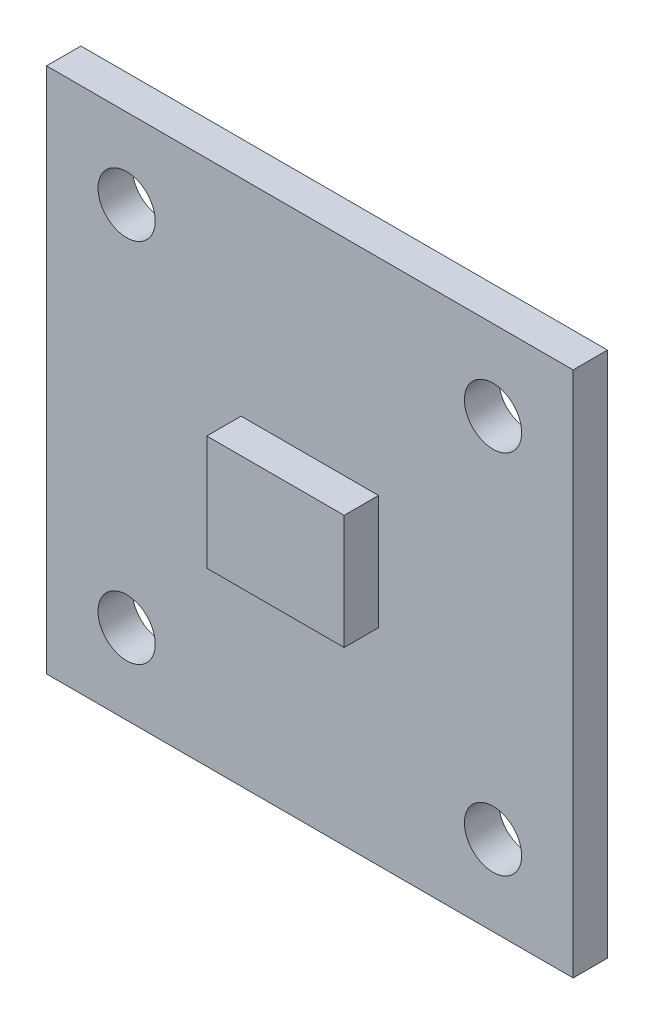
SolidWorks part; units mm, degrees
ref_plane "前视基准面" through (0, 0, 0) normal (0, 0, 1) x (1, 0, 0)
ref_plane "上视基准面" through (0, 0, 0) normal (0, 1, 0) x (1, 0, 0)
ref_plane "右视基准面" through (0, 0, 0) normal (1, 0, 0) x (0, 0, -1)
sketch "草图1" plane through (0, 0, 0) normal (0, 0, 1) x (1, 0, 0)
  line L1 (-11.5, -11.5) -> (11.5, -11.5)
  line L2 (-11.5, -11.5) -> (-11.5, 11.5)
  line L3 (-11.5, 11.5) -> (11.5, 11.5)
  line L4 (11.5, -11.5) -> (11.5, 11.5)
  line L5 (-11.5, -11.5) -> (11.5, 11.5) construction
  line L6 (-11.5, 11.5) -> (11.5, -11.5) construction
  line L7 (-8, -8) -> (8, -8) construction
  line L8 (-8, -8) -> (-8, 8) construction
  line L9 (-8, 8) -> (8, 8) construction
  line L10 (8, -8) -> (8, 8) construction
  line L11 (-8, -8) -> (8, 8) construction
  line L12 (-8, 8) -> (8, -8) construction
  circle A0 centre (-8, 8) radius 1.25
  circle A1 centre (8, 8) radius 1.25
  circle A2 centre (8, -8) radius 1.25
  circle A3 centre (-8, -8) radius 1.25
  point P0 (0, 0)
  point P6 (0, 0)
  dimension "D3" = 2.5
  dimension "D1" = 23
  dimension "D2" = 16
extrude "凸台-拉伸1" add sketch "草图1" along normal mid plane 1.5
sketch "草图2" plane through (0, 0, 0.75) normal (0, 0, 1) x (1, 0, 0)
  line L1 (-3, -2.5) -> (3, -2.5)
  line L2 (-3, -2.5) -> (-3, 2.5)
  line L3 (-3, 2.5) -> (3, 2.5)
  line L4 (3, -2.5) -> (3, 2.5)
  line L5 (-3, -2.5) -> (3, 2.5) construction
  line L6 (-3, 2.5) -> (3, -2.5) construction
  point P0 (0, 0)
  dimension "D1" = 6
  dimension "D2" = 5
extrude "凸台-拉伸2" add sketch "草图2" along normal blind 1.5
sketch "草图3" plane through (0, 0, 0) normal (0, 0, 1) x (1, 0, 0)
  circle A0 centre (0, 0) radius 5
  dimension "D1" = 10
